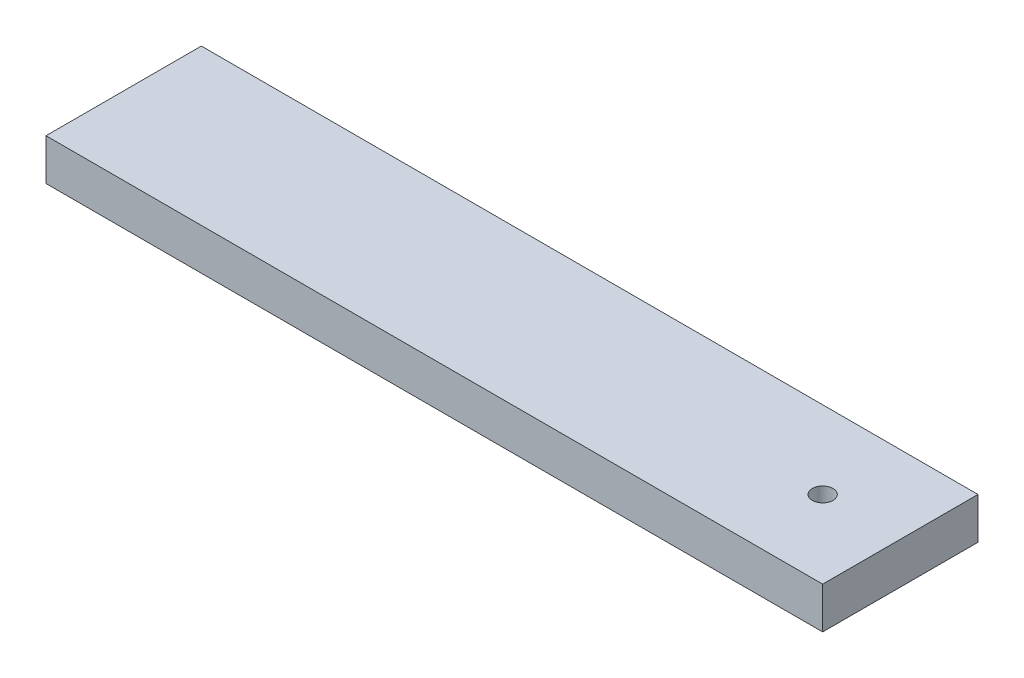
SolidWorks part; units mm, degrees
ref_plane "Front Plane" through (0, 0, 0) normal (0, 0, 1) x (1, 0, 0)
ref_plane "Top Plane" through (0, 0, 0) normal (0, 1, 0) x (1, 0, 0)
ref_plane "Right Plane" through (0, 0, 0) normal (1, 0, 0) x (0, 0, -1)
sketch "Sketch1" plane through (0, 0, 0) normal (0, 1, 0) x (1, 0, 0)
  line L1 (-75, 15) -> (75, 15)
  line L2 (-75, 15) -> (-75, -15)
  line L3 (-75, -15) -> (75, -15)
  line L4 (75, 15) -> (75, -15)
  line L5 (-75, 15) -> (75, -15) construction
  line L6 (-75, -15) -> (75, 15) construction
  circle A0 centre (60, 0) radius 2
  point P0 (0, 0)
  dimension "D3" = 4
  dimension "D4" = 15
  dimension "D1" = 30
  dimension "D2" = 150
  dimension "D5" = 15
extrude "Boss-Extrude1" add sketch "Sketch1" along normal blind 8
